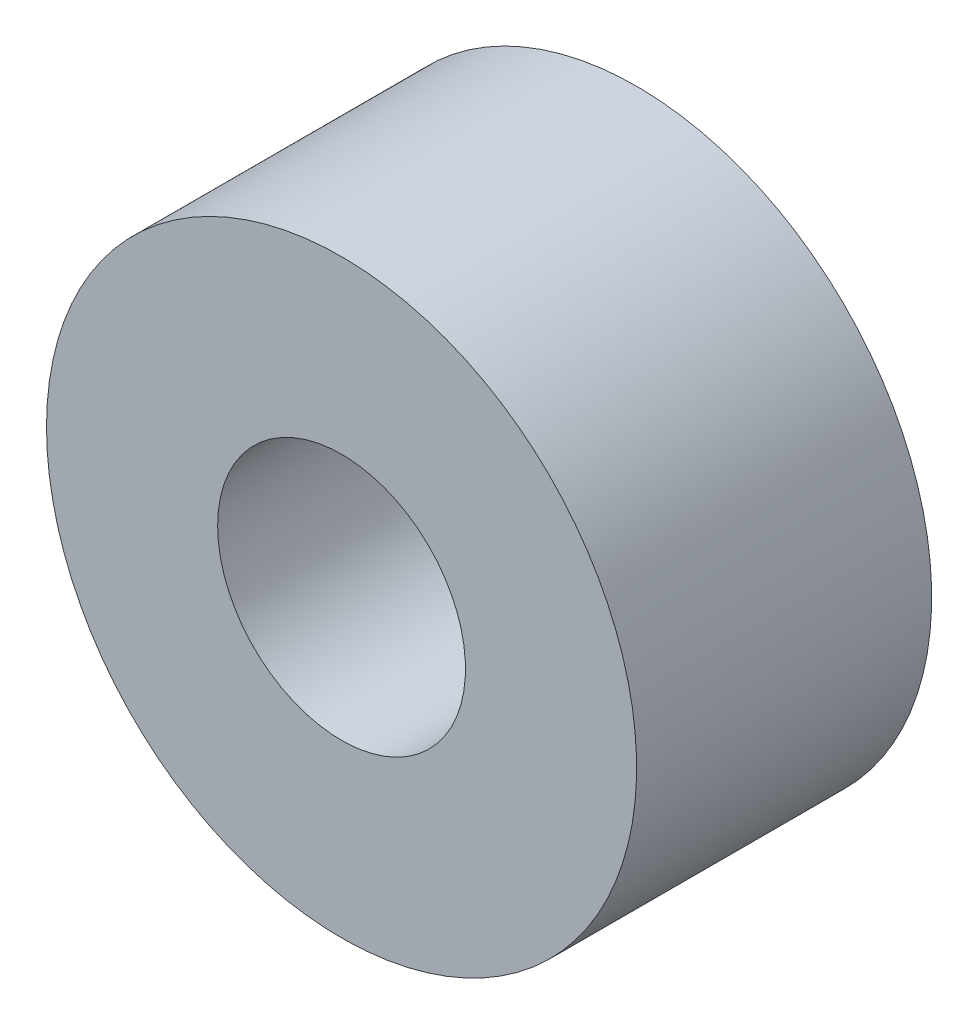
SolidWorks part; units mm, degrees
ref_plane "Front Plane" through (0, 0, 0) normal (0, 0, 1) x (1, 0, 0)
ref_plane "Top Plane" through (0, 0, 0) normal (0, 1, 0) x (1, 0, 0)
ref_plane "Right Plane" through (0, 0, 0) normal (1, 0, 0) x (0, 0, -1)
sketch "Sketch1" plane through (0, 0, 0) normal (0, 0, 1) x (1, 0, 0)
  circle A0 centre (0, 0) radius 9.525
  circle A1 centre (0, 0) radius 4.0005
  dimension "OD" = 19.05
  dimension "ID" = 8.001
extrude "Extrude1" add sketch "Sketch1" along normal mid plane 9.525
sketch "Sketch2" plane through (0, 0, 0) normal (1, 0, 0) x (0, 0, -1)
  line L0 (-4.7625, -4.0005) -> (4.7625, -4.0005) construction
  line L3 (4.7625, 4.0005) -> (-4.7625, 4.0005) construction
  line L5 (-4.7625, -4.0005) -> (4.7625, -4.0005)
  line L6 (4.7625, 4.0005) -> (-4.7625, 4.0005)
sketch "Sketch4" plane through (0, 0, 4.7625) normal (0, 0, 1) x (1, 0, 0)
  line L0 (0, 0) -> (-2.8288, 2.8288)
  line L1 (0, -2.1828) -> (0, 2.1828) construction
  circle A0 centre (0, 0) radius 4.0005 construction
  dimension "D1" = 45
